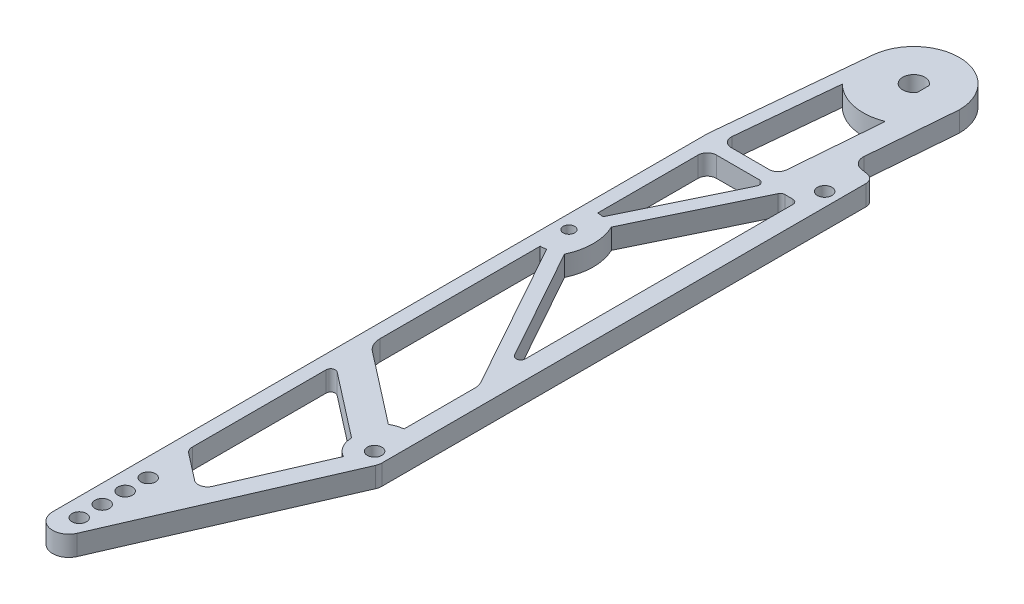
SolidWorks part; units mm, degrees
material "6061-T6 (SS)"
ref_plane "X-Y Datum" through (0, 0, 0) normal (0, 0, 1) x (1, 0, 0)
ref_plane "X-Z Datum" through (0, 0, 0) normal (0, 1, 0) x (1, 0, 0)
ref_plane "Y-Z Datum" through (0, 0, 0) normal (1, 0, 0) x (0, 0, -1)
other "Graphic1" [suppressed]
other "Graphic (Closed) -1" [suppressed]
sketch "Sketch2" plane through (0, 0, 0) normal (0, 1, 0) x (1, 0, 0)
  line L5 (13.4859, -162.4108) -> (-11.43, -143.082) construction
  line L8 (0, 0) -> (0, -24.13) construction
  line L11 (15.1556, -28.0184) -> (13.2387, -27.713)
  line L15 (-16.51, -221.3289) -> (-16.51, -40.4661)
  line L22 (-7.9887, -223.1013) -> (16.9799, -165.6775)
  line L23 (17.2959, -164.1583) -> (17.2959, -30.5268)
  line L33 (10.4385, -167.9818) -> (-0.5342, -193.2173)
  line L44 (-7.4473, -76.0744) -> (7.5755, -45.0536)
  line L45 (8.7185, -44.3372) -> (10.9459, -44.3372)
  line L46 (12.2159, -45.6072) -> (12.2159, -119.4928)
  line L47 (9.8359, -120.11) -> (-7.4473, -89.0256)
  line L49 (-12.4315, -37.7433) -> (-9.7554, -9.9996)
  line L51 (5.1277, -12.9949) -> (3.0693, -38.194)
  line L53 (0.5377, -40.5272) -> (-9.9032, -40.5272)
  line L56 (1.663, -44.3372) -> (-10.16, -44.3372)
  line L57 (13.7382, -24.5776) -> (0, 0) construction
  line L58 (10.5738, -24.3191) -> (12.5603, 0)
  line L59 (-12.7, -149.6154) -> (-12.7, -186.5441)
  line L63 (7.1359, -162.4108) -> (-10.6516, -148.612)
  line L64 (-12.7, -74.6125) -> (-12.7, -46.8772)
  line L65 (2.8061, -46.1607) -> (-11.056, -74.7846)
  line L66 (-16.4983, -40.2222) -> (-12.5023, 1.2059)
  line L67 (-4.4204, -194.2114) -> (-11.7169, -188.551)
  line L68 (5.8058, -44.3372) -> (-12.7, -82.55) construction
  line L69 (-1.7326, -64.2739) -> (-5.1616, -62.6133) construction
  line L70 (8.9236, -154.0495) -> (-10.7338, -138.8001)
  line L71 (12.2159, -152.9708) -> (12.2159, -133.548)
  line L72 (11.5758, -131.0794) -> (-11.086, -90.3217)
  line L75 (-12.7, -134.7862) -> (-12.7, -90.4875)
  line L76 (2.6, -1.5945) -> (2.6, 1.5945)
  circle A0 centre (0, 0) radius 3.05
  circle A2 centre (-11.43, -219.075) radius 2
  circle A3 centre (-11.43, -212.725) radius 2
  circle A4 centre (-11.43, -206.375) radius 2
  circle A5 centre (-11.43, -200.025) radius 2
  circle A7 centre (0, 0) radius 12.5603 construction
  circle A8 centre (-12.7, -82.55) radius 1.5875
  circle A12 centre (13.4859, -38.1) radius 2
  arc A13 (-12.5023, 1.2059) -> (12.5603, 0) centre (0, 0) cw
  arc A14 (-7.4473, -89.0256) -> (-7.4473, -76.0744) centre (-20.962, -82.55) ccw
  circle A16 centre (24.0125, -14.7036) radius 3.175 construction
  arc A17 (24.0125, -14.7036) -> (13.7382, -24.5776) centre (0, 0) cw construction
  circle A18 centre (13.7382, -24.5776) radius 3.175 construction
  arc A19 (13.2387, -27.713) -> (10.5738, -24.3191) centre (13.7382, -24.5776) cw
  arc A20 (15.1556, -28.0184) -> (17.2959, -30.5268) centre (14.7559, -30.5268) cw
  circle A21 centre (13.4859, -162.4108) radius 2
  arc A24 (10.4385, -167.9818) -> (7.1359, -162.4108) centre (13.4859, -162.4108) cw
  arc A25 (-16.51, -221.3289) -> (-7.9887, -223.1013) centre (-12.065, -221.3289) ccw
  arc A26 (-12.7, -74.6125) -> (-11.056, -74.7846) centre (-12.7, -82.55) cw
  arc A28 (5.1277, -12.9949) -> (-9.7554, -9.9996) centre (0, 0) cw
  arc A31 (-10.16, -44.3372) -> (-12.7, -46.8772) centre (-10.16, -46.8772) ccw
  arc A32 (-12.4315, -37.7433) -> (-9.9032, -40.5272) centre (-9.9032, -37.9872) ccw
  arc A33 (0.5377, -40.5272) -> (3.0693, -38.194) centre (0.5377, -37.9872) ccw
  arc A36 (-12.7, -149.6154) -> (-10.6516, -148.612) centre (-11.43, -149.6154) cw
  arc A37 (9.8359, -120.11) -> (12.2159, -119.4928) centre (10.9459, -119.4928) ccw
  arc A38 (7.5755, -45.0536) -> (8.7185, -44.3372) centre (8.7185, -45.6072) cw
  arc A39 (10.9459, -44.3372) -> (12.2159, -45.6072) centre (10.9459, -45.6072) cw
  arc A40 (1.663, -44.3372) -> (2.8061, -46.1607) centre (1.663, -45.6072) cw
  arc A50 (17.2959, -164.1583) -> (16.9799, -165.6775) centre (13.4859, -164.1583) cw
  arc A52 (-16.4983, -40.2222) -> (-16.51, -40.4661) centre (-13.97, -40.4661) ccw
  arc A53 (-12.7, -186.5441) -> (-11.7169, -188.551) centre (-10.16, -186.5441) ccw
  arc A54 (-4.4204, -194.2114) -> (-0.5342, -193.2173) centre (-2.8635, -192.2045) ccw
  arc A55 (12.2159, -152.9708) -> (8.9236, -154.0495) centre (13.4859, -162.4108) ccw
  arc A56 (-11.086, -90.3217) -> (-12.7, -90.4875) centre (-12.7, -82.55) cw
  arc A57 (-12.7, -134.7862) -> (-10.7338, -138.8001) centre (-7.62, -134.7862) ccw
  arc A58 (11.5758, -131.0794) -> (12.2159, -133.548) centre (7.1359, -133.548) cw
  point P30 (17.2959, -28.3595)
  point P44 (-3.4471, -63.4436)
  point P45 (-1.8376, -196.215)
  point P48 (12.2159, -82.55)
  point P75 (-3.05, 0)
  point P88 (-12.7, -44.3372)
  point P91 (-12.7, -40.5272)
  point P104 (12.2159, -124.3904)
  point P107 (7.9224, -44.3372)
  point P110 (12.2159, -44.3372)
  point P120 (17.2959, -164.9508)
  dimension "D1" = 6.1
  dimension "D6" = 4
  dimension "D12" = 24.13
  dimension "D5" = 25.1206
  dimension "D14" = 3.175
  dimension "D19" = 4
  dimension "D20" = 6.35
  dimension "D24" = 3.81
  dimension "D50" = 14.986
  dimension "D51" = 8.262
  dimension "D42" = 3.81
  dimension "D62" = 6.35
  dimension "D63" = 29.204
  dimension "D27" = 2.54
  dimension "D44" = 4
  dimension "D18" = 4.445
  dimension "D34" = 3.81
  dimension "D36" = 6.35
  dimension "D33" = 13.97
  dimension "D38" = 3.81
  dimension "D39" = 8.89
  dimension "D48" = 2.54
  dimension "D49" = 1.27
  dimension "D52" = 3.81
  dimension "D53" = 3.81
  dimension "D54" = 9.525
  dimension "D58" = 2.54
  dimension "D59" = 3.81
  dimension "D64" = 5.65
  dimension "D29" = 7.9375
  dimension "D31" = 3.81
  dimension "D41" = 2.54
  dimension "D55" = 7.9375
  dimension "D57" = 5.08
  dimension "D7" = 6.35
  dimension "D8" = 6.35
  dimension "D9" = 6.35
  dimension "D10" = 5.08
  dimension "D11" = 5.08
  dimension "D13" = 4.1084
  dimension "D15" = 82.55
  dimension "D16" = 12.7
  dimension "D17" = 13.7382
  dimension "D21" = 136.5913
  dimension "D22" = 38.1
  dimension "D23" = 13.4859
  dimension "D25" = 5.08
  dimension "D26" = 3.81
  dimension "D28" = 40.5272
  dimension "D30" = 2.54
  dimension "D32" = 3.81
  dimension "D35" = 3.81
  dimension "D37" = 16.51
  dimension "D40" = 23.5
  dimension "D43" = 200.025
  dimension "D45" = 6.35
  dimension "D46" = 6.35
  dimension "D47" = 4.2935
  dimension "D56" = 3.81
  dimension "D60" = 24.0125
  dimension "D61" = 14.7036
extrude "Boss-Extrude1" add sketch "Sketch2" along normal blind 5.588 contours L66 A52 L15 A25 L22 A50 L23 A20 L11 A19 L58 A13 A54 L67 A53 L59 A36 L63 A24 L33 L56 A40 L65 A26 L64 A31 L45 A39 L46 A37 L47 A14 L44 A38 A0 A2 A3 A4 A5 A8 | L76 A0
sketch "Sketch6" plane through (-16.51, 0, 0) normal (-1, 0, 0) x (0, 0, 1)
  line L0 (183.2289, 5.588) -> (183.2289, 0)
  line L3 (221.3289, 5.588) -> (221.3289, 0) construction
  line L4 (221.3289, 5.588) -> (40.4661, 5.588) construction
  line L5 (221.3289, 0) -> (40.4661, 0) construction
  dimension "D1" = 38.1
split line "Split Line2"
sketch "Sketch7" plane through (0, 0, 0) normal (0, -1, 0) x (1, 0, 0)
  line L0 (0, 0) -> (0, 23.7661) construction
